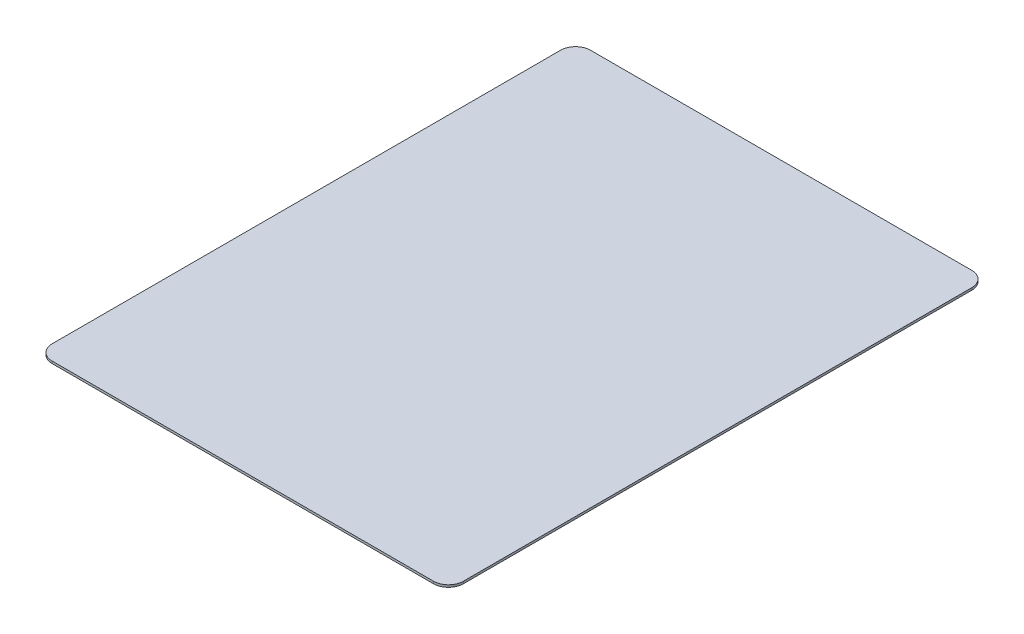
SolidWorks part; units mm, degrees
ref_plane "Front Plane" through (0, 0, 0) normal (0, 0, 1) x (1, 0, 0)
ref_plane "Top Plane" through (0, 0, 0) normal (0, 1, 0) x (1, 0, 0)
ref_plane "Right Plane" through (0, 0, 0) normal (1, 0, 0) x (0, 0, -1)
sketch "Sketch1" plane through (0, 0, 0) normal (0, 1, 0) x (1, 0, 0)
  line L1 (-255, 360) -> (255, 360)
  line L2 (-275, 340) -> (-275, -340)
  line L3 (-255, -360) -> (255, -360)
  line L4 (275, 340) -> (275, -340)
  line L5 (-275, 360) -> (275, -360) construction
  line L6 (-275, -360) -> (275, 360) construction
  arc A0 (-255, -360) -> (-275, -340) centre (-255, -340) cw
  arc A1 (275, -340) -> (255, -360) centre (255, -340) cw
  arc A2 (275, 340) -> (255, 360) centre (255, 340) ccw
  arc A3 (-255, 360) -> (-275, 340) centre (-255, 340) ccw
  point P0 (0, 0)
  dimension "D3" = 20
  dimension "D1" = 720
  dimension "D2" = 550
extrude "Boss-Extrude1" add sketch "Sketch1" along normal blind 3
equation "\"corner_radius\"= 20mm"
equation "\"hole_spacing\"= 50mm"
equation "\"D3@Sketch1\"=\"corner_radius\""
equation "\"panel_thickness\"= 3mm"
equation "\"D1@Boss-Extrude1\"=\"panel_thickness\""
